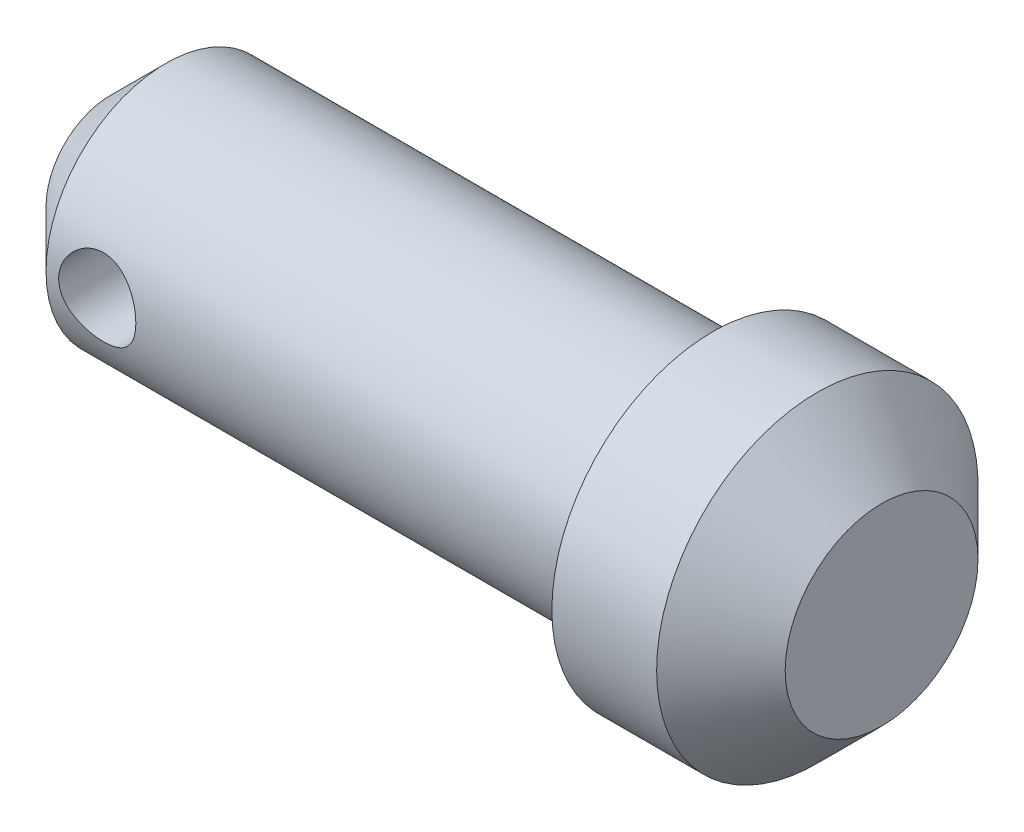
SolidWorks part; units mm, degrees
ref_plane "Front Plane" through (0, 0, 0) normal (0, 0, 1) x (1, 0, 0)
ref_plane "Top Plane" through (0, 0, 0) normal (0, 1, 0) x (1, 0, 0)
ref_plane "Right Plane" through (0, 0, 0) normal (1, 0, 0) x (0, 0, -1)
sketch "Sketch2" plane through (0, 0, 0) normal (0, 0, 1) x (1, 0, 0)
  line L0 (0, 0) -> (120, 0)
  line L1 (120, 0) -> (120, -15)
  line L2 (120, -15) -> (110, -25)
  line L3 (110, -25) -> (93.7, -25)
  line L4 (93.7, -25) -> (93.7, -18.7)
  line L5 (8.7, -18.7) -> (93.7, -18.7)
  line L6 (0, 0) -> (0, -10)
  line L7 (0, -10) -> (8.7, -18.7)
  dimension "D1" = 120
  dimension "D2" = 10
  dimension "60mm" = 85
  dimension "D3" = 15
  dimension "D4" = 135
  dimension "D5" = 10
revolve "Revolve1" add sketch "Sketch2" angle 360 about L0
sketch "Sketch3" plane through (0, 0, 0) normal (0, 0, 1) x (1, 0, 0)
  circle A0 centre (16.6694, 0) radius 6
  dimension "D1" = 12
extrude "Cut-Extrude1" cut sketch "Sketch3" against normal through all both and the other way through all
